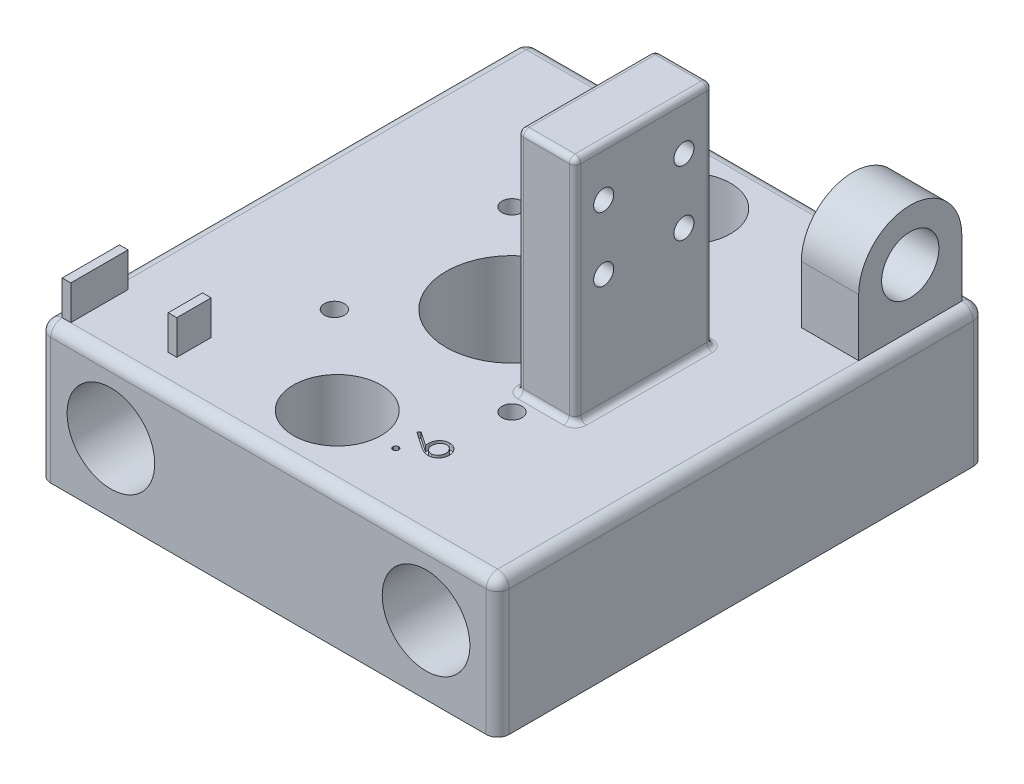
SolidWorks part; units mm, degrees
ref_plane "Alzado" through (0, 0, 0) normal (0, 0, 1) x (1, 0, 0)
ref_plane "Planta" through (0, 0, 0) normal (0, 1, 0) x (1, 0, 0)
ref_plane "Vista lateral" through (0, 0, 0) normal (1, 0, 0) x (0, 0, -1)
sketch "Croquis1" plane through (0, 0, 0) normal (0, 0, 1) x (1, 0, 0)
  line L1 (-40, -12) -> (40, -12)
  line L2 (-40, -12) -> (-40, 12)
  line L3 (-40, 12) -> (40, 12)
  line L4 (40, -12) -> (40, 12)
  line L5 (-40, -12) -> (40, 12) construction
  line L6 (-40, 12) -> (40, -12) construction
  point P0 (0, 0)
extrude "Saliente-Extruir1" add sketch "Croquis1" along normal blind 85
sketch "Croquis2" plane through (0, 0, 0) normal (0, 0, -1) x (-1, 0, 0)
  line L0 (40, -12) -> (27.5, -12) construction
  line L1 (40, -12) -> (-40, -12) construction
  line L2 (27.5, -12) -> (-27.5, -12) construction
  line L3 (-27.5, -12) -> (-40, -12) construction
  line L4 (27.5, -12) -> (27.5, 0) construction
  line L5 (-27.5, -12) -> (-27.5, 0) construction
  circle A0 centre (-27.5, 0) radius 7.65
  circle A1 centre (27.5, 0) radius 7.65
extrude "Cortar-Extruir1" cut sketch "Croquis2" against normal through all
fillet "Redondeo1" radius 2 8 edges at (-40, 0, 85) (-40, 0, 0) (-40, 12, 42.5) (40, 0, 85) (0, 12, 85) (40, 0, 0) (0, 12, 0) (40, 12, 42.5)
sketch "Croquis3" plane through (0, 12, 0) normal (0, 1, 0) x (1, 0, 0)
  line L0 (-38, -2) -> (0, -2) construction
  line L1 (38, -2) -> (-38, -2) construction
  line L2 (-38, -83) -> (0, -83) construction
  line L3 (0, -2) -> (0, -12) construction
  line L4 (-38, -83) -> (38, -83) construction
  line L5 (0, -83) -> (0, -73) construction
  circle A0 centre (0, -12) radius 7.65
  circle A1 centre (0, -73) radius 7.65
extrude "Cortar-Extruir2" cut sketch "Croquis3" against normal through all
sketch "Croquis5" plane through (0, 12, 0) normal (0, 1, 0) x (1, 0, 0)
  circle A0 centre (0, -42.5) radius 1.6273
extrude "Cortar-Extruir3" cut sketch "Croquis5" against normal blind 1
sketch "Croquis6" plane through (0, 12, 0) normal (0, 1, 0) x (1, 0, 0)
  circle A0 centre (0, -42.5) radius 11.5
  dimension "D1" = 23
extrude "Cortar-Extruir4" cut sketch "Croquis6" against normal blind 32
sketch "Croquis7" plane through (0, -12, 0) normal (0, -1, 0) x (1, 0, 0)
  circle A0 centre (15.5, 58) radius 1.75
  circle A1 centre (15.5, 27) radius 1.75
  circle A2 centre (-15.5, 27) radius 1.75
  circle A3 centre (-15.5, 58) radius 1.75
  point P0 (0, 42.5)
extrude "Cortar-Extruir5" cut sketch "Croquis7" against normal blind 30
sketch "Croquis8" plane through (0, 12, 0) normal (0, 1, 0) x (1, 0, 0)
  line L0 (0, -42.5) -> (13, -42.5) construction
  line L1 (13, -42.5) -> (13, -30.5) construction
  line L2 (13, -30.5) -> (23, -30.5) construction
  line L3 (23, -30.5) -> (23, -54.5) construction
  line L4 (23, -54.5) -> (13, -54.5) construction
  line L6 (13, -30.5) -> (23, -30.5)
  line L7 (13, -30.5) -> (13, -54.5)
  line L8 (13, -54.5) -> (23, -54.5)
  line L9 (23, -30.5) -> (23, -54.5)
  dimension "D1" = 12
  dimension "D2" = 12
extrude "Saliente-Extruir2" add sketch "Croquis8" along normal blind 40
fillet "Redondeo2" radius 1 8 edges at (18, 52, 30.5) (23, 52, 42.5) (23, 32, 30.5) (23, 32, 54.5) (13, 32, 30.5) (18, 52, 54.5) (13, 52, 42.5) (13, 32, 54.5)
fillet "Redondeo3" radius 1 8 edges at (13.2929, 12, 54.2071) (13.2929, 12, 30.7929) (22.7071, 12, 30.7929) (22.7071, 12, 54.2071) (13, 12, 42.5) (18, 12, 30.5) (23, 12, 42.5) (18, 12, 54.5)
sketch "Croquis9" plane through (13, 0, 0) normal (-1, 0, 0) x (0, 0, 1)
  line L0 (31.5, 51) -> (31.5, 13) construction
  line L1 (42.5, 51) -> (42.5, 23.2511) construction
  line L2 (53.5, 51) -> (31.5, 51) construction
  circle A0 centre (35.5, 43.555) radius 1.75
  circle A1 centre (35.5, 32.305) radius 1.75
  circle A2 centre (49.5, 43.555) radius 1.75
  circle A3 centre (49.5, 32.305) radius 1.75
  point P3 (31.5, 32)
  dimension "D1" = 4
  dimension "D3" = 11.25
  dimension "D2" = 4
extrude "Cortar-Extruir6" cut sketch "Croquis9" against normal up to next
sketch "Croquis10" plane through (0, 12, 0) normal (0, 1, 0) x (1, 0, 0)
  line L1 (-38, -83) -> (38, -83) construction
  line L2 (10.4305, -83) -> (10.4305, -59.5) construction
  text T0 "9." font "Century Gothic" height 6
extrude "Cortar-Extruir7" cut sketch "Croquis10" against normal blind 1
sketch "Croquis11" plane through (0, 12, 0) normal (0, 1, 0) x (1, 0, 0)
  line L0 (-38, -2) -> (-38, -83) construction
  line L1 (-38, -83) -> (-36.5, -83)
  line L2 (-38, -83) -> (38, -83) construction
  line L8 (-38, -83) -> (-38, -73)
  line L9 (-38, -73) -> (-36.5, -73)
  line L10 (-36.5, -83) -> (-36.5, -73)
  point P1 (-37.25, -83)
  dimension "D1" = 1.5
  dimension "D2" = 0
  dimension "D3" = 10
extrude "Saliente-Extruir3" add sketch "Croquis11" along normal blind 6
sketch "Croquis12" plane through (0, 12, 0) normal (0, 1, 0) x (1, 0, 0)
  line L0 (-36.5, -83) -> (-36.5, -73) construction
  line L8 (-23.5, -79) -> (-22, -79)
  line L9 (-23.5, -79) -> (-23.5, -73)
  line L10 (-23.5, -73) -> (-22, -73)
  line L11 (-22, -79) -> (-22, -73)
  dimension "D1" = 13
  dimension "D4" = 6
extrude "Saliente-Extruir4" add sketch "Croquis12" along normal blind 6
sketch "Croquis13" plane through (0, 12, 0) normal (0, 1, 0) x (1, 0, 0)
  line L0 (38, -2) -> (28, -2)
  line L1 (38, -2) -> (38, -20)
  line L2 (28, -2) -> (28, -20)
  line L3 (38, -20) -> (28, -20)
  line L4 (38, -2) -> (-38, -2) construction
  dimension "D1" = 18
  dimension "D2" = 10
extrude "Saliente-Extruir5" add sketch "Croquis13" along normal blind 10
sketch "Croquis14" plane through (38, 0, 0) normal (1, 0, 0) x (0, 0, -1)
  line L0 (-20, 22) -> (-2, 22) construction
  circle A0 centre (-11, 22) radius 9
extrude "Saliente-Extruir6" add sketch "Croquis14" against normal blind 10
sketch "Croquis15" plane through (38, 0, 0) normal (1, 0, 0) x (0, 0, -1)
  circle A0 centre (-11, 22) radius 5
extrude "Cortar-Extruir8" cut sketch "Croquis15" against normal blind 10
